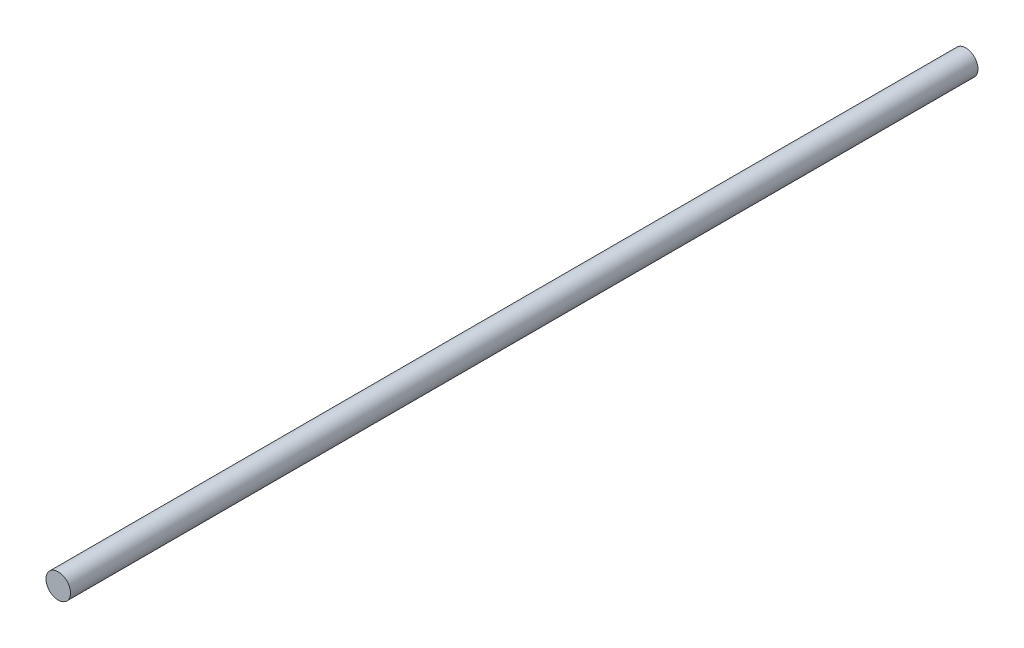
SolidWorks part; units mm, degrees
material "Plain Carbon Steel"
ref_plane "Front Plane" through (0, 0, 0) normal (0, 0, 1) x (1, 0, 0)
ref_plane "Top Plane" through (0, 0, 0) normal (0, 1, 0) x (1, 0, 0)
ref_plane "Right Plane" through (0, 0, 0) normal (1, 0, 0) x (0, 0, -1)
sketch "Sketch1" plane through (0, 0, 0) normal (0, 0, 1) x (1, 0, 0)
  circle A0 centre (0, 0) radius 1.5875
  dimension "D1" = 3.175
extrude "Boss-Extrude1" add sketch "Sketch1" along normal blind 117.475
